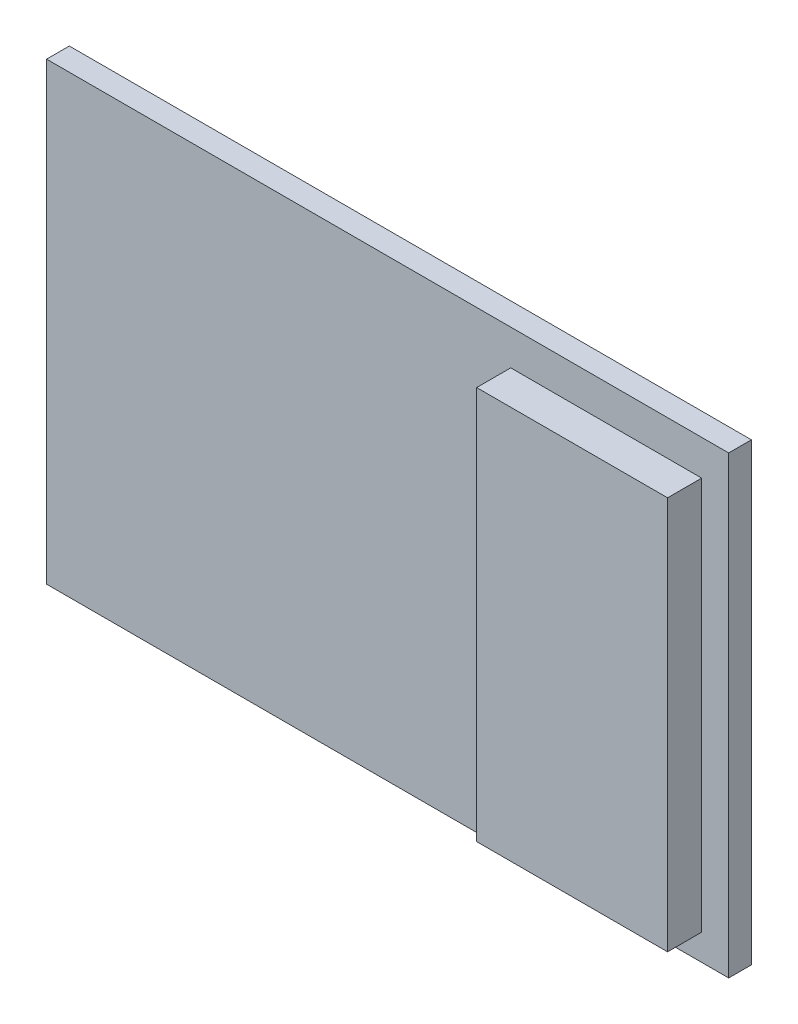
SolidWorks part; units mm, degrees
ref_plane "Plan de face" through (0, 0, 0) normal (0, 0, 1) x (1, 0, 0)
ref_plane "Plan de dessus" through (0, 0, 0) normal (0, 1, 0) x (1, 0, 0)
ref_plane "Plan de droite" through (0, 0, 0) normal (1, 0, 0) x (0, 0, -1)
sketch "Esquisse1" plane through (0, 0, 0) normal (0, 0, 1) x (1, 0, 0)
  line L1 (-30, 20) -> (30, 20)
  line L2 (-30, 20) -> (-30, -20)
  line L3 (-30, -20) -> (30, -20)
  line L4 (30, 20) -> (30, -20)
  line L5 (-30, 20) -> (30, -20) construction
  line L6 (-30, -20) -> (30, 20) construction
  point P0 (0, 0)
  dimension "D1" = 60
  dimension "D2" = 40
extrude "Boss.-Extru.1" add sketch "Esquisse1" along normal blind 2
sketch "Esquisse2" plane through (0, 0, 2) normal (0, 0, 1) x (1, 0, 0)
  line L1 (10.8305, 16.8955) -> (27.626, 16.8955)
  line L2 (10.8305, 16.8955) -> (10.8305, -17.6953)
  line L3 (10.8305, -17.6953) -> (27.626, -17.6953)
  line L4 (27.626, 16.8955) -> (27.626, -17.6953)
extrude "Boss.-Extru.2" add sketch "Esquisse2" along normal blind 3
